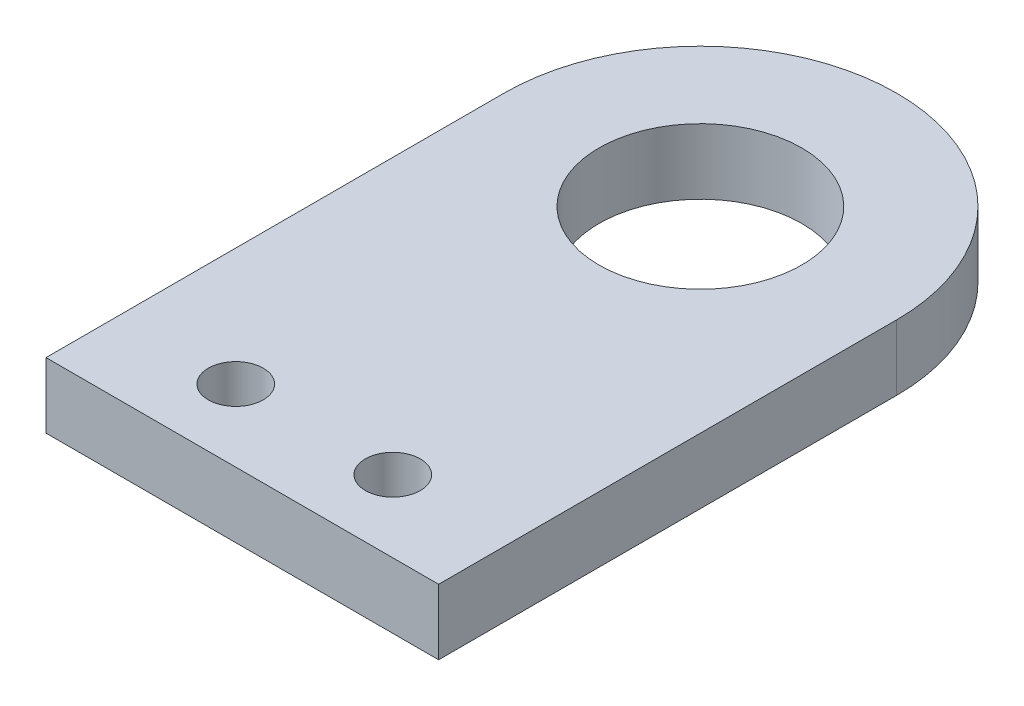
SolidWorks part; units mm, degrees
ref_plane "前视基准面" through (0, 0, 0) normal (0, 0, 1) x (1, 0, 0)
ref_plane "上视基准面" through (0, 0, 0) normal (0, 1, 0) x (1, 0, 0)
ref_plane "右视基准面" through (0, 0, 0) normal (1, 0, 0) x (0, 0, -1)
other "Configuration Table"
sketch "草图1" plane through (0, 0, 0) normal (0, 1, 0) x (1, 0, 0)
  line L0 (-15, 0) -> (15, 0)
  line L1 (15, 0) -> (15, 35)
  line L2 (-15, 0) -> (-15, 35)
  line L3 (0, -28.4509) -> (0, 58.1647) construction
  line L4 (-15, 35) -> (15, 35) construction
  line L5 (-27.315, 5.5) -> (32.5533, 5.5) construction
  arc A0 (15, 35) -> (-15, 35) centre (0, 35) ccw
  circle A1 centre (-6, 5.5) radius 2.1
  circle A2 centre (6, 5.5) radius 2.1
  circle A3 centre (0, 35) radius 7.75
  dimension "D3" = 4.2
  dimension "D4" = 12
  dimension "D6" = 15.5
  dimension "D1" = 30
  dimension "D2" = 5.5
  dimension "D5" = 35
extrude "凸台-拉伸1" add sketch "草图1" along normal blind 5 contours L1 A0 L2 L0 A3 A1 A2
